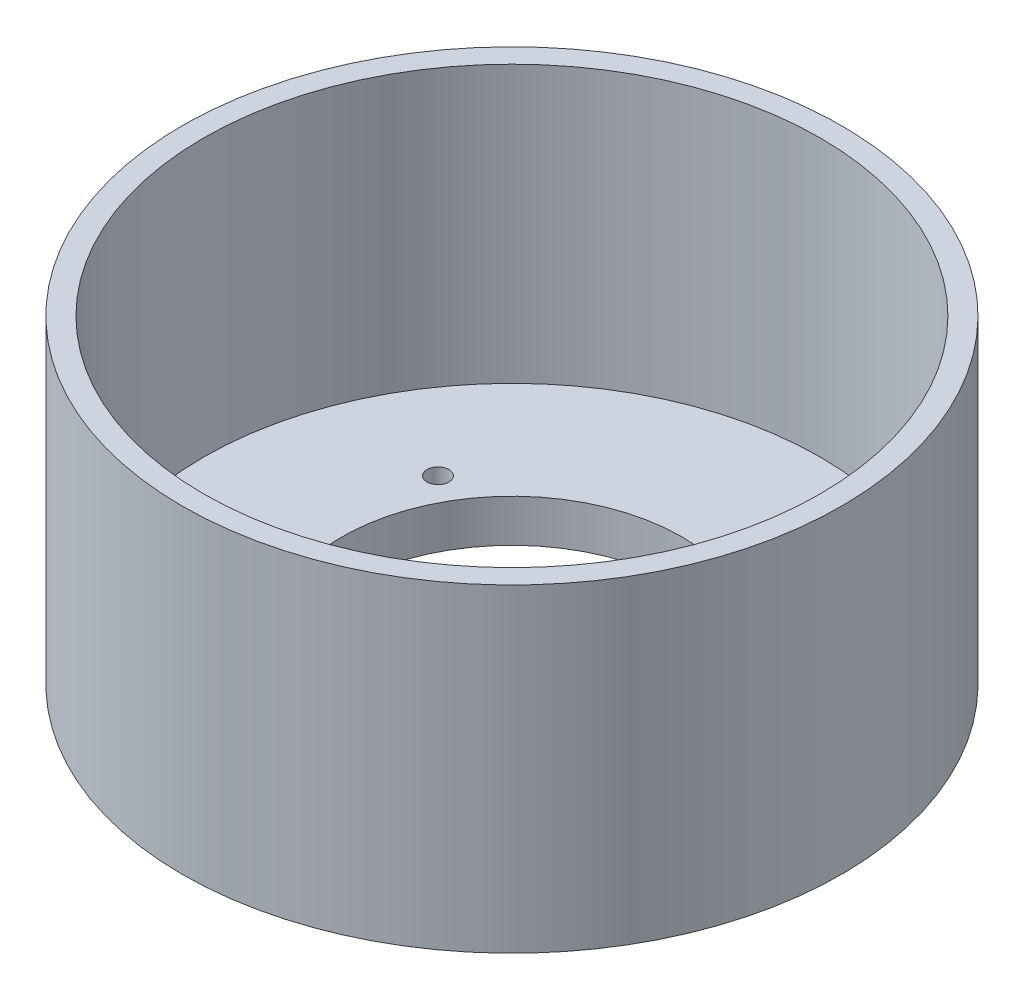
SolidWorks part; units mm, degrees
ref_plane "前视基准面" through (0, 0, 0) normal (0, 0, 1) x (1, 0, 0)
ref_plane "上视基准面" through (0, 0, 0) normal (0, 1, 0) x (1, 0, 0)
ref_plane "右视基准面" through (0, 0, 0) normal (1, 0, 0) x (0, 0, -1)
sketch "草图1" plane through (0, 0, 0) normal (0, 1, 0) x (1, 0, 0)
  circle A0 centre (0, 0) radius 31
  dimension "D1" = 62
extrude "凸台-拉伸1" add sketch "草图1" along normal blind 30
cosmetic thread "装饰螺纹线2" parameters "D1"=14.5, "D2"=58.376
ref_plane "基准面2" through (0, 5, 0) normal (0, -1, 0) x (-1, 0, 0)
sketch "草图5" plane through (0, 5, 0) normal (0, -1, 0) x (-1, 0, 0)
  circle A0 centre (0, 0) radius 16
  point P0 (0, 0)
  dimension "D1" = 32
extrude "切除-拉伸3" cut sketch "草图5" along normal through all and the other way through all
ref_plane "基准面3" through (0, 30, 0) normal (0, 1, 0) x (1, 0, 0)
sketch "草图6" plane through (0, 30, 0) normal (0, 1, 0) x (1, 0, 0)
  circle A0 centre (0, 0) radius 29
  dimension "D1" = 58
extrude "切除-拉伸4" cut sketch "草图6" against normal blind 26 contours A0
ref_plane "基准面4" through (0, 0, 0) normal (0, 1, 0) x (1, 0, 0)
ref_plane "定位面" through (0, 4, 0) normal (0, 1, 0) x (1, 0, 0)
sketch "草图8" plane through (0, 4, 0) normal (0, 1, 0) x (1, 0, 0)
  line L1 (16.455, -9.5) -> (-16.455, -9.5) construction
  line L2 (16.455, -9.5) -> (16.455, 9.5) construction
  line L3 (16.455, 9.5) -> (-16.455, 9.5) construction
  line L4 (-16.455, -9.5) -> (-16.455, 9.5) construction
  line L5 (16.455, -9.5) -> (-16.455, 9.5) construction
  line L6 (16.455, 9.5) -> (-16.455, -9.5) construction
  point P0 (0, 0)
  dimension "D1" = 32.91
  dimension "D2" = 19
hole_wizard "M2.5 螺纹孔1" positions "草图9" profile "草图10" tap size "M2.5" standard "GB" end condition through all
sketch "草图9" plane through (0, 4, 0) normal (0, 1, 0) x (1, 0, 0)
  point P0 (-16.455, 9.5)
  point P3 (16.455, 9.5)
  point P6 (16.455, -9.5)
  point P9 (-16.455, -9.5)
sketch "草图10" plane through (-16.455, 4, -9.5) normal (1, 0, 0) x (0, 0, 1)
  line L0 (0, 0) -> (0, 4)
  line L1 (0, 4) -> (1.025, 4)
  line L2 (1.025, 4) -> (1.025, 0)
  line L5 (1.025, 0) -> (0, 0)
  line L11 (0, -6.35) -> (0, 107.95) construction
  dimension "通孔螺纹孔钻头直径" = 2.05
  dimension "通孔螺纹孔钻头深度" = 4
cosmetic thread "孔螺蚊线1" parameters "D2"=2.5
cosmetic thread "孔螺蚊线2" parameters "D2"=2.5
cosmetic thread "孔螺蚊线3" parameters "D2"=2.5
cosmetic thread "孔螺蚊线4" parameters "D2"=2.5
